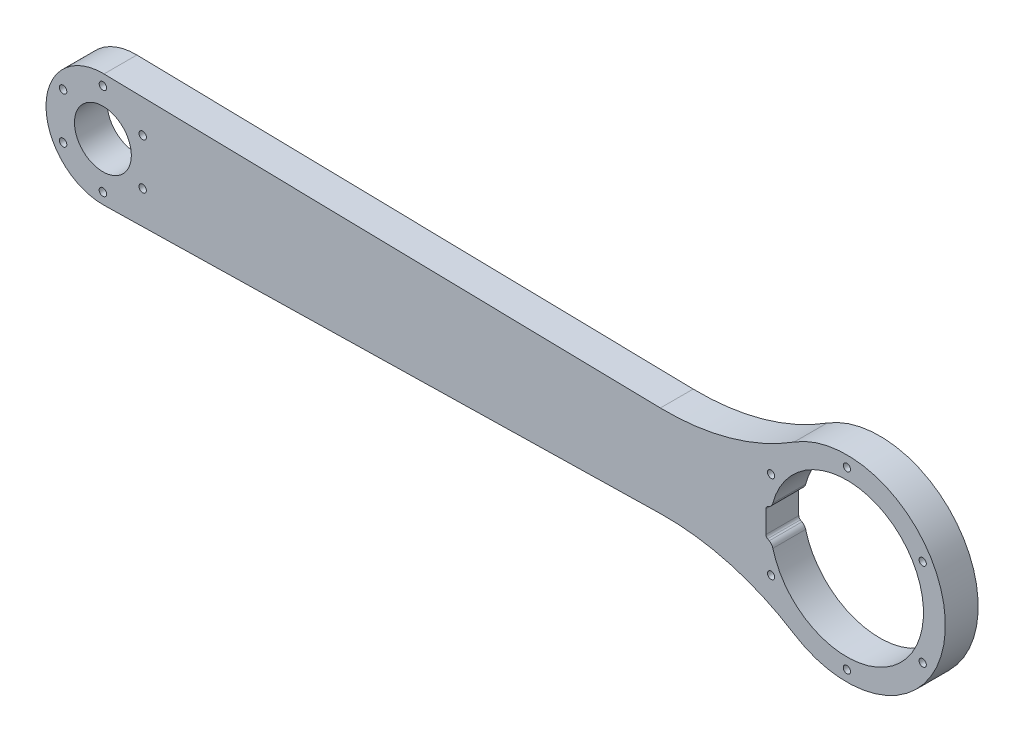
SolidWorks part; units mm, degrees
ref_plane "前视基准面" through (0, 0, 0) normal (0, 0, 1) x (1, 0, 0)
ref_plane "上视基准面" through (0, 0, 0) normal (0, 1, 0) x (1, 0, 0)
ref_plane "右视基准面" through (0, 0, 0) normal (1, 0, 0) x (0, 0, -1)
sketch "草图1" plane through (0, 0, 0) normal (0, 0, 1) x (1, 0, 0)
  line L0 (0, 0) -> (0, 46.9214) construction
  line L1 (0, 0) -> (75.8039, 0) construction
  line L2 (-85.2451, 20.9004) -> (-339.4791, 25.9948)
  line L3 (-85.2451, -20.9004) -> (-339.4791, -25.9948)
  line L4 (-35.5001, 6.7904) -> (-36.238, 6.3734)
  line L5 (-37, 5.0675) -> (-37, -5.0675)
  line L7 (-358.1865, 10.5) -> (-358.1865, -10.5) construction
  line L8 (-30.9669, 5.9447) -> (-28.6669, 5.9455) construction
  line L9 (-35.5001, -6.7904) -> (-36.238, -6.3734)
  line L10 (-29.6741, 7.5384) -> (-26.4741, 7.5394) construction
  line L11 (-340, -21) -> (-321.8135, -10.5) construction
  line L12 (-321.8135, -10.5) -> (-321.8135, 10.5) construction
  line L13 (-321.8135, 10.5) -> (-340, 21) construction
  line L14 (-340, 21) -> (-358.1865, 10.5) construction
  line L15 (-358.1865, -10.5) -> (-340, -21) construction
  circle A0 centre (0, 40) radius 1.65
  arc A1 (0, 38.35) -> (0, 41.65) centre (0, 40) ccw construction
  circle A2 centre (34.641, 20) radius 1.65
  circle A3 centre (34.641, -20) radius 1.65
  arc A4 (34.641, 18.35) -> (34.641, 21.65) centre (34.641, 20) ccw construction
  circle A5 centre (0, -40) radius 1.65
  arc A6 (0, -41.65) -> (0, -38.35) centre (0, -40) ccw construction
  circle A7 centre (-34.641, 20) radius 1.65
  arc A8 (-34.641, 21.65) -> (-34.641, 18.35) centre (-34.641, 20) ccw construction
  circle A9 centre (-34.641, -20) radius 1.65
  circle A10 centre (0, 0) radius 35 construction
  arc A12 (-33.8381, 8.9432) -> (-33.8381, -8.9432) centre (0, 0) cw
  arc A13 (-24.1088, 37.9969) -> (-24.1088, -37.9969) centre (0, 0) cw
  circle A14 centre (-340, 0) radius 13
  arc A15 (-85.2451, -20.9004) -> (-24.1088, -37.9969) centre (-83.0414, -130.8783) cw
  arc A16 (-24.1088, 37.9969) -> (-85.2451, 20.9004) centre (-83.0414, 130.8783) cw
  arc A17 (-339.4791, 25.9948) -> (-339.4791, -25.9948) centre (-340, 0) ccw
  arc A18 (-35.5001, -6.7904) -> (-33.8381, -8.9432) centre (-37.2219, -9.8375) cw
  arc A19 (-33.8381, 8.9432) -> (-35.5001, 6.7904) centre (-37.2219, 9.8375) cw
  arc A20 (-36.238, -6.3734) -> (-37, -5.0675) centre (-35.5, -5.0675) cw
  arc A21 (-36.238, 6.3734) -> (-37, 5.0675) centre (-35.5, 5.0675) ccw
  circle A22 centre (-340, 0) radius 21 construction
  circle A23 centre (-340, 0) radius 18.1865 construction
  circle A24 centre (-340, 21) radius 1.7
  circle A25 centre (-358.1865, 10.5) radius 1.7
  circle A26 centre (-358.1865, -10.5) radius 1.7
  circle A27 centre (-340, -21) radius 1.7
  circle A28 centre (-321.8135, -10.5) radius 1.7
  circle A29 centre (-321.8135, 10.5) radius 1.7
  point P48 (-40.3113, -20)
  point P51 (-40.3113, 20)
  point P60 (-37, 0)
  point P63 (-35, 0)
  point P70 (-34.1789, -7.537)
  point P73 (-34.1789, 7.537)
  point P76 (-37, -5.9428)
  point P79 (-37, 5.9428)
  dimension "D1" = 70
  dimension "D2" = 45
  dimension "D4" = 110
  dimension "D5" = 26
  dimension "D7" = 26
  dimension "D9" = 3.5
  dimension "D10" = 1.5
  dimension "D11" = 42
  dimension "D12" = 3.4
  dimension "D3" = 20
  dimension "D6" = 340
  dimension "D8" = 2
  dimension "D13" = 340
extrude "凸台-拉伸1" add sketch "草图1" along normal blind 15 contours L2 A17 L3 A15 A13 A16
sketch "草图2" plane through (0, 0, 0) normal (0, 0, 1) x (1, 0, 0)
  line L0 (-376.6145, -430.0012) -> (356.6217, 230.2077) construction
